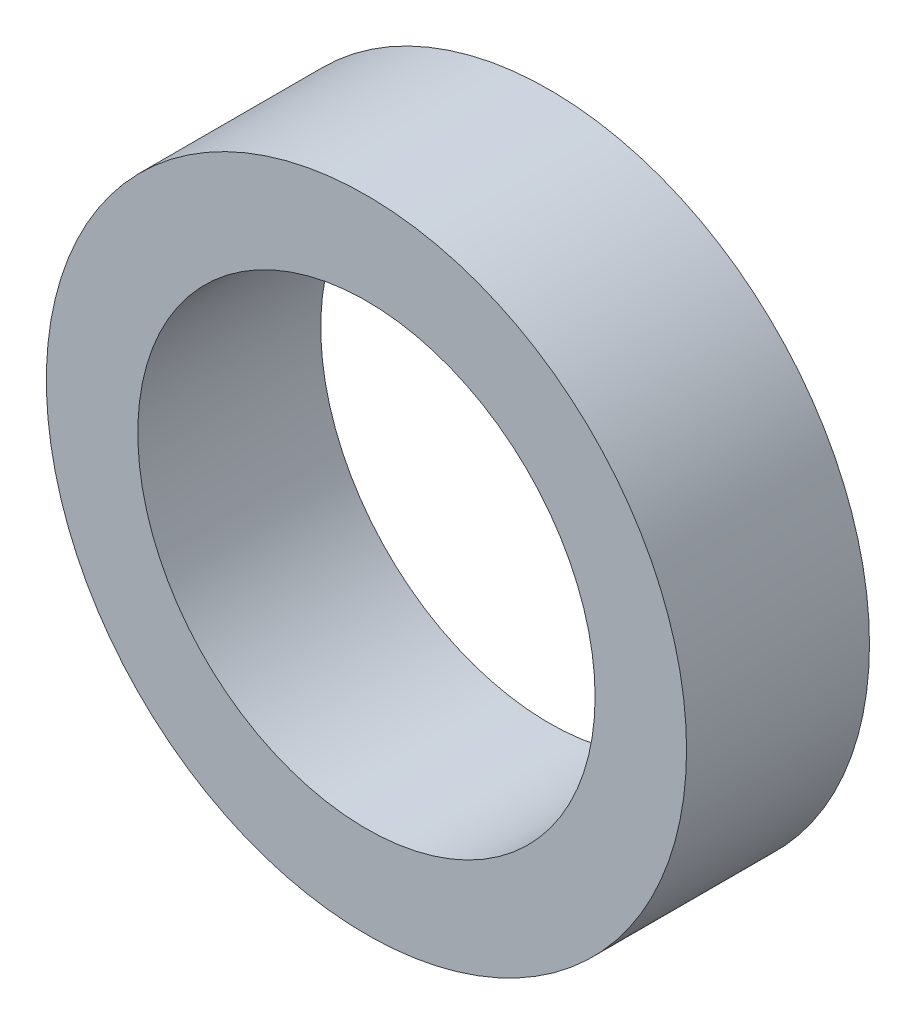
SolidWorks part; units mm, degrees
ref_plane "前视基准面" through (0, 0, 0) normal (0, 0, 1) x (1, 0, 0)
ref_plane "上视基准面" through (0, 0, 0) normal (0, 1, 0) x (1, 0, 0)
ref_plane "右视基准面" through (0, 0, 0) normal (1, 0, 0) x (0, 0, -1)
sketch "草图1" plane through (0, 0, 0) normal (0, 0, 1) x (1, 0, 0)
  circle A0 centre (0, 0) radius 7
  circle A1 centre (0, 0) radius 5
  dimension "D1" = 10
  dimension "D2" = 14
extrude "凸台-拉伸1" add sketch "草图1" along normal blind 4
